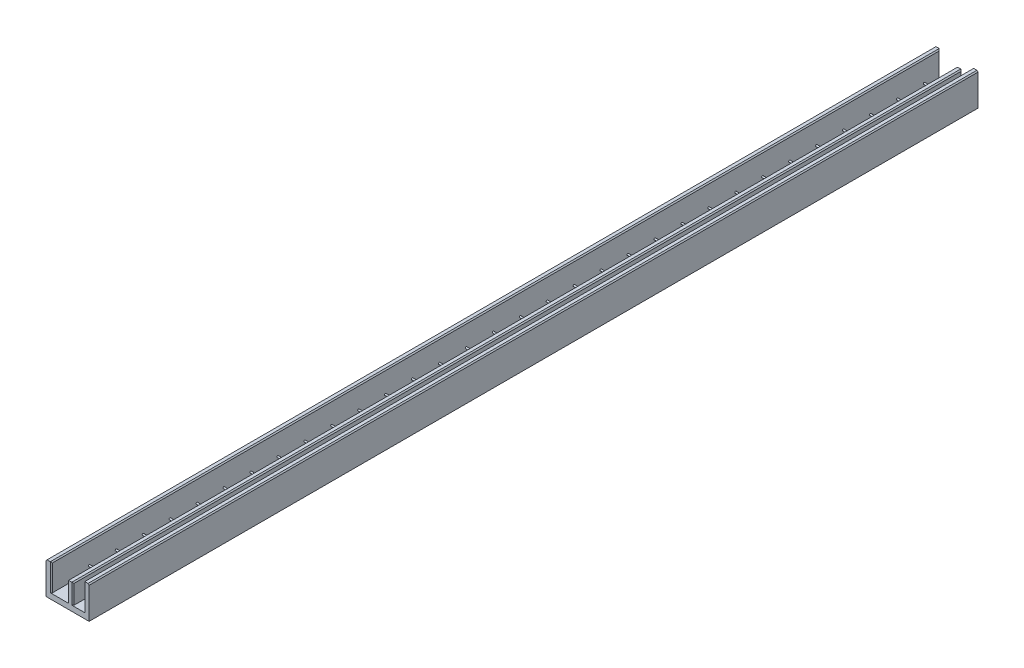
SolidWorks part; units mm, degrees
ref_plane "Alzado" through (0, 0, 0) normal (0, 0, 1) x (1, 0, 0)
ref_plane "Planta" through (0, 0, 0) normal (0, 1, 0) x (1, 0, 0)
ref_plane "Vista lateral" through (0, 0, 0) normal (1, 0, 0) x (0, 0, -1)
sketch "Croquis1" plane through (0, 0, 0) normal (0, 0, 1) x (1, 0, 0)
  line L0 (0, 0) -> (-800, 0)
  line L1 (-800, 0) -> (-800, 600)
  line L2 (-800, 600) -> (-700, 600)
  line L3 (-700, 600) -> (-700, 100)
  line L4 (-700, 100) -> (-400, 100)
  line L5 (-400, 100) -> (-400, 470)
  line L6 (-400, 470) -> (-300, 470)
  line L7 (-300, 470) -> (-300, 100)
  line L8 (-300, 100) -> (-100, 100)
  line L9 (-100, 100) -> (-100, 600)
  line L10 (-100, 600) -> (0, 600)
  line L11 (0, 600) -> (0, 0)
  dimension "D1" = 800
  dimension "D2" = 600
  dimension "D3" = 100
  dimension "D4" = 500
  dimension "D5" = 300
  dimension "D6" = 370
  dimension "D7" = 100
  dimension "D8" = 370
  dimension "D9" = 200
extrude "Saliente-Extruir1" add sketch "Croquis1" along normal blind 16500
chamfer "Chaflán2" distance 20 angle 45 14 edges at (-100, 350, 0) (0, 600, 8250) (-700, 350, 0) (-700, 600, 8250) (-700, 350, 16500) (-100, 350, 16500) (-300, 285, 0) (-300, 285, 16500) (-300, 470, 8250) (-400, 285, 0) (-400, 285, 16500) (-400, 470, 8250) (-800, 600, 8250) (-100, 600, 8250)
sketch "Croquis2" plane through (-800, 0, 0) normal (-1, 0, 0) x (0, 0, 1)
  line L0 (0, 580) -> (0, 0) construction
  circle A0 centre (300, 200) radius 15
  dimension "D3" = 30
  dimension "D1" = 300
extrude "Saliente-Extruir2" add sketch "Croquis2" against normal up to surface (700 mm away) up to face at (-100, 340, 8250)
pattern_linear "MatrizL1" count 32 spacing 500 along (0, 0, 1) of "Saliente-Extruir2"
